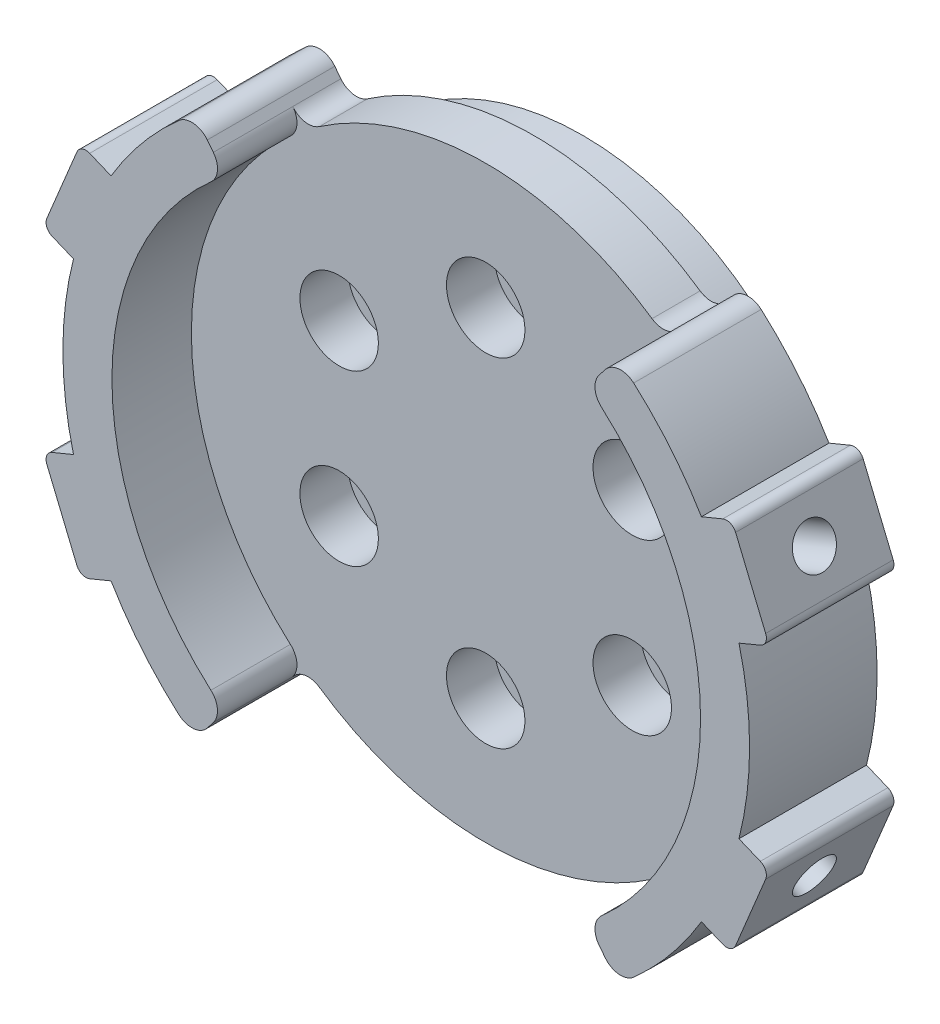
SolidWorks part; units mm, degrees
ref_plane "前视基准面" through (0, 0, 0) normal (0, 0, 1) x (1, 0, 0)
ref_plane "上视基准面" through (0, 0, 0) normal (0, 1, 0) x (1, 0, 0)
ref_plane "右视基准面" through (0, 0, 0) normal (1, 0, 0) x (0, 0, -1)
other "Configuration Table"
sketch "草图1" plane through (0, 0, 0) normal (0, 0, 1) x (1, 0, 0)
  circle A1 centre (0, 0) radius 17.25 construction
  circle A2 centre (0, 17.25) radius 2.1
  circle A8 centre (0, 0) radius 30
  circle A9 centre (14.9389, 8.625) radius 2.1
  circle A10 centre (14.9389, -8.625) radius 2.1
  circle A11 centre (0, -17.25) radius 2.1
  circle A12 centre (-14.9389, -8.625) radius 2.1
  circle A13 centre (-14.9389, 8.625) radius 2.1
  point P16 (0, 0)
  point P21 (0, 0)
  dimension "D1" = 60
  dimension "D2" = 34.5
  dimension "D3" = 4.2
  dimension "D4" = 6
extrude "凸台-拉伸1" add sketch "草图1" along normal blind 5
sketch "草图2" plane through (0, 0, 5) normal (0, 0, 1) x (1, 0, 0)
  line L0 (0, 0) -> (0, 35)
  line L1 (0, 0) -> (-35, 0)
  line L2 (0, 0) -> (-21.5482, 27.5804)
  line L3 (0, 0) -> (-21.5482, -27.5804)
  line L4 (0, 0) -> (21.5482, -27.5804)
  line L5 (0, 0) -> (21.5482, 27.5804)
  circle A0 centre (0, 0) radius 35
  circle M8 centre (0, 0) radius 30
  dimension "D2" = 70
  dimension "D1" = 52
  dimension "D3" = 52
extrude "凸台-拉伸2" add sketch "草图2" along normal blind 8 and the other way blind 5 contours L1 A0 L3 M8 | L2 A0 L1 M8 | L4 A0 L5 M8
sketch "草图3" plane through (0, 0, 13) normal (0, 0, 1) x (1, 0, 0)
  line L0 (0, 0) -> (0, 30)
  line L1 (0, 0) -> (-35, 0)
  line L2 (0, 0) -> (-32.3358, 13.3939)
  line L3 (-33.194, 19.1614) -> (-37.0208, 9.9226)
  line L4 (-33.194, 19.1614) -> (-30.0907, 17.8759)
  line L5 (-37.0208, 9.9226) -> (-33.9175, 8.6371)
  line L6 (0, 0) -> (-35.1074, 14.542)
  line L7 (-33.194, -19.1614) -> (-30.0907, -17.8759)
  line L8 (-37.0208, -9.9226) -> (-33.9175, -8.6371)
  line L9 (-33.194, -19.1614) -> (-37.0208, -9.9226)
  line L10 (33.194, -19.1614) -> (30.0907, -17.8759)
  line L11 (33.194, -19.1614) -> (37.0208, -9.9226)
  line L12 (-18.4698, 23.6403) -> (-21.5482, 27.5804)
  line L13 (-21.5482, -27.5804) -> (-18.4698, -23.6403)
  line L14 (-18.4698, 23.6403) -> (-21.5482, 27.5804)
  line L15 (-21.5482, -27.5804) -> (-18.4698, -23.6403)
  line L16 (37.0208, -9.9226) -> (33.9175, -8.6371)
  line L17 (37.0208, 9.9226) -> (33.9175, 8.6371)
  line L18 (33.194, 19.1614) -> (37.0208, 9.9226)
  line L19 (33.194, 19.1614) -> (30.0907, 17.8759)
  line L22 (18.4698, -23.6403) -> (21.5482, -27.5804)
  line L23 (21.5482, 27.5804) -> (18.4698, 23.6403)
  line L24 (18.4698, -23.6403) -> (21.5482, -27.5804)
  line L25 (21.5482, 27.5804) -> (18.4698, 23.6403)
  arc A0 (-21.5482, 27.5804) -> (-21.5482, -27.5804) centre (0, 0) ccw construction
  arc A3 (-18.4698, 23.6403) -> (-18.4698, -23.6403) centre (0, 0) ccw
  arc A4 (-18.4698, 23.6403) -> (-18.4698, -23.6403) centre (0, 0) ccw
  arc A5 (-18.4698, -23.6403) -> (18.4698, -23.6403) centre (0, 0) ccw
  arc A6 (18.4698, -23.6403) -> (18.4698, 23.6403) centre (0, 0) ccw
  arc A7 (18.4698, 23.6403) -> (-18.4698, 23.6403) centre (0, 0) ccw
  arc A8 (-18.4698, 23.6403) -> (-18.4698, -23.6403) centre (0, 0) ccw
  arc A9 (-18.4698, -23.6403) -> (18.4698, -23.6403) centre (0, 0) ccw
  arc A10 (18.4698, -23.6403) -> (18.4698, 23.6403) centre (0, 0) ccw
  arc A11 (18.4698, 23.6403) -> (-18.4698, 23.6403) centre (0, 0) ccw
  arc A12 (-21.5482, 27.5804) -> (-21.5482, -27.5804) centre (0, 0) ccw
  arc A13 (-18.4698, 23.6403) -> (-18.4698, -23.6403) centre (0, 0) ccw
  arc A14 (-21.5482, 27.5804) -> (-21.5482, -27.5804) centre (0, 0) ccw
  arc A15 (21.5482, -27.5804) -> (21.5482, 27.5804) centre (0, 0) ccw
  arc A16 (18.4698, -23.6403) -> (18.4698, 23.6403) centre (0, 0) ccw
  arc A17 (21.5482, -27.5804) -> (21.5482, 27.5804) centre (0, 0) ccw
  arc A18 (18.4698, -23.6403) -> (18.4698, 23.6403) centre (0, 0) ccw
  point P17 (-35.1074, 14.542)
  arc M23 (-21.5482, 27.5804) -> (-21.5482, -27.5804) centre (0, 0) ccw
  dimension "D2" = 67.5
  dimension "D3" = 10
  dimension "D4" = 38
  dimension "D1" = 0
  dimension "D5" = 0
  dimension "D6" = 0
extrude "凸台-拉伸3" add sketch "草图3" against normal through all contours A17 L17 L18 L19 | A17 L10 L11 L16 | L9 L7 L8 M23 | L6 L4 L3 M23 | L6 L3 L5 M23
sketch "草图4" plane through (-35.1074, 14.542, 0) normal (-0.9239, 0.3827, 0) x (0, 0, 1)
  line L0 (0, 0) -> (13, 0)
  line L1 (6.5, -5) -> (6.5, 5)
  line L4 (13, -5) -> (13, 5)
  line L5 (13, 5) -> (0, 5)
  line L6 (0, 5) -> (0, -5)
  line L7 (0, -5) -> (13, -5)
  line L8 (13, -5) -> (13, 5)
  line L9 (13, 5) -> (0, 5)
  line L10 (0, 5) -> (0, -5)
  line L11 (0, -5) -> (13, -5)
  circle A0 centre (6.5, 0) radius 2.1
  dimension "D2" = 4.2
  dimension "D1" = 0
extrude "切除-拉伸2" cut sketch "草图4" against normal blind 7.5 contours L0 A0 L1 | L1 A0 L0 | L0 A0 L1 | L1 A0 L0
sketch "草图5" plane through (-35.1074, -14.542, 0) normal (-0.9239, -0.3827, 0) x (0, 0, 1)
  line L0 (0, 0) -> (13, 0)
  line L1 (13, -5) -> (13, 5) construction
  line L2 (6.5, 5) -> (6.5, -5)
  line L3 (0, 5) -> (13, 5) construction
  line L4 (0, -5) -> (13, -5) construction
  circle A0 centre (6.5, 0) radius 2.1
  dimension "D1" = 4.2
extrude "切除-拉伸3" cut sketch "草图5" against normal blind 7.5 contours L2 A0 L0 | L0 A0 L2 | L2 A0 L0 | L0 A0 L2
sketch "草图6" plane through (35.1074, 14.542, 0) normal (0.9239, 0.3827, 0) x (0, 0, -1)
  line L0 (-13, 0) -> (0, 0)
  line L4 (-13, 5) -> (-13, -5)
  line L5 (-13, -5) -> (0, -5)
  line L6 (0, -5) -> (0, 5)
  line L7 (0, 5) -> (-13, 5)
  line L8 (-13, 5) -> (-13, -5)
  line L9 (-13, -5) -> (0, -5)
  line L10 (0, -5) -> (0, 5)
  line L11 (0, 5) -> (-13, 5)
  circle A0 centre (-6.5, 0) radius 2.1
  dimension "D2" = 4.2
  dimension "D1" = 0
extrude "切除-拉伸4" cut sketch "草图6" against normal blind 7.5 contours L0 A0 | L0 A0
sketch "草图7" plane through (35.1074, -14.542, 0) normal (0.9239, -0.3827, 0) x (0, 0, -1)
  line L0 (-13, 0) -> (0, 0)
  line L4 (-13, 5) -> (-13, -5)
  line L5 (-13, -5) -> (0, -5)
  line L6 (0, -5) -> (0, 5)
  line L7 (0, 5) -> (-13, 5)
  line L8 (-13, 5) -> (-13, -5)
  line L9 (-13, -5) -> (0, -5)
  line L10 (0, -5) -> (0, 5)
  line L11 (0, 5) -> (-13, 5)
  circle A0 centre (-6.5, 0) radius 2.1
  dimension "D2" = 4.2
  dimension "D1" = 0
extrude "切除-拉伸5" cut sketch "草图7" against normal blind 7.5 contours L0 A0 | L0 A0
fillet "圆角1" radius 2 8 edges at (21.5482, -27.5804, 6.5) (18.4698, -23.6403, 9) (-21.5482, -27.5804, 6.5) (-18.4698, -23.6403, 9) (-18.4698, 23.6403, 9) (-21.5482, 27.5804, 6.5) (18.4698, 23.6403, 9) (21.5482, 27.5804, 6.5)
fillet "圆角2" radius 2 4 edges at (-18.4698, 23.6403, 2.5) (18.4698, 23.6403, 2.5) (18.4698, -23.6403, 2.5) (-18.4698, -23.6403, 2.5)
sketch "草图8" plane through (0, 0, 0) normal (0, 0, -1) x (-1, 0, 0)
  circle A0 centre (0, 0) radius 27.5
  circle A2 centre (0, 17.25) radius 2.1
  circle A3 centre (0, 17.25) radius 2.1
  circle A4 centre (-14.9389, 8.625) radius 2.1
  circle A5 centre (-14.9389, 8.625) radius 2.1
  circle A6 centre (-14.9389, -8.625) radius 2.1
  circle A7 centre (-14.9389, -8.625) radius 2.1
  circle A8 centre (0, -17.25) radius 2.1
  circle A9 centre (0, -17.25) radius 2.1
  circle A10 centre (14.9389, -8.625) radius 2.1
  circle A11 centre (14.9389, -8.625) radius 2.1
  circle A12 centre (14.9389, 8.625) radius 2.1
  circle A13 centre (14.9389, 8.625) radius 2.1
  dimension "D7" = 55
  dimension "D1" = 0
  dimension "D2" = 0
  dimension "D3" = 0
  dimension "D4" = 0
  dimension "D5" = 0
  dimension "D6" = 0
extrude "凸台-拉伸4" add sketch "草图8" along normal blind 5 contours A0 | A7 | A9 | A5 | A13 | A11 | A3
sketch "草图9" plane through (0, 0, 5) normal (0, 0, 1) x (1, 0, 0)
  circle A0 centre (-14.9389, 8.625) radius 4
  circle A1 centre (0, 17.25) radius 2.1
  circle A2 centre (0, 17.25) radius 2.1
  circle A3 centre (14.9389, 8.625) radius 2.1
  circle A4 centre (14.9389, 8.625) radius 2.1
  circle A5 centre (14.9389, -8.625) radius 2.1
  circle A6 centre (14.9389, -8.625) radius 2.1
  circle A7 centre (0, -17.25) radius 2.1
  circle A8 centre (0, -17.25) radius 2.1
  circle A9 centre (-14.9389, -8.625) radius 2.1
  circle A10 centre (-14.9389, -8.625) radius 2.1
  circle A11 centre (-14.9389, 8.625) radius 2.1
  circle A12 centre (-14.9389, 8.625) radius 2.1
  circle A13 centre (0, 17.25) radius 4
  circle A14 centre (14.9389, 8.625) radius 4
  circle A15 centre (14.9389, -8.625) radius 4
  circle A16 centre (0, -17.25) radius 4
  circle A17 centre (-14.9389, -8.625) radius 4
  arc A24 (19.6627, 25.167) -> (19.9113, 22.4397) centre (21.2387, 23.9357) ccw
  arc A25 (16.9562, 24.7485) -> (19.6627, 25.167) centre (18.0866, 26.3984) ccw
  arc A26 (16.9562, 24.7485) -> (-16.9562, 24.7485) centre (0, 0) ccw
  arc A27 (-19.6627, 25.167) -> (-16.9562, 24.7485) centre (-18.0866, 26.3984) ccw
  arc A28 (-19.9113, 22.4397) -> (-19.6627, 25.167) centre (-21.2387, 23.9357) ccw
  arc A29 (-19.9113, 22.4397) -> (-19.9113, -22.4397) centre (0, 0) ccw
  arc A30 (-19.6627, -25.167) -> (-19.9113, -22.4397) centre (-21.2387, -23.9357) ccw
  arc A31 (-16.9562, -24.7485) -> (-19.6627, -25.167) centre (-18.0866, -26.3984) ccw
  arc A32 (-16.9562, -24.7485) -> (16.9562, -24.7485) centre (0, 0) ccw
  arc A33 (19.6627, -25.167) -> (16.9562, -24.7485) centre (18.0866, -26.3984) ccw
  arc A34 (19.9113, -22.4397) -> (19.6627, -25.167) centre (21.2387, -23.9357) ccw
  arc A35 (19.9113, -22.4397) -> (19.9113, 22.4397) centre (0, 0) ccw
  arc A36 (19.6627, 25.167) -> (19.9113, 22.4397) centre (21.2387, 23.9357) ccw
  arc A37 (16.9562, 24.7485) -> (19.6627, 25.167) centre (18.0866, 26.3984) ccw
  arc A38 (16.9562, 24.7485) -> (-16.9562, 24.7485) centre (0, 0) ccw
  arc A39 (-19.6627, 25.167) -> (-16.9562, 24.7485) centre (-18.0866, 26.3984) ccw
  arc A40 (-19.9113, 22.4397) -> (-19.6627, 25.167) centre (-21.2387, 23.9357) ccw
  arc A41 (-19.9113, 22.4397) -> (-19.9113, -22.4397) centre (0, 0) ccw
  arc A42 (-19.6627, -25.167) -> (-19.9113, -22.4397) centre (-21.2387, -23.9357) ccw
  arc A43 (-16.9562, -24.7485) -> (-19.6627, -25.167) centre (-18.0866, -26.3984) ccw
  arc A44 (-16.9562, -24.7485) -> (16.9562, -24.7485) centre (0, 0) ccw
  arc A45 (19.6627, -25.167) -> (16.9562, -24.7485) centre (18.0866, -26.3984) ccw
  arc A46 (19.9113, -22.4397) -> (19.6627, -25.167) centre (21.2387, -23.9357) ccw
  arc A47 (19.9113, -22.4397) -> (19.9113, 22.4397) centre (0, 0) ccw
  circle M19 centre (-14.9389, -8.625) radius 2.1
  circle M20 centre (14.9389, -8.625) radius 2.1
  circle M21 centre (0, 17.25) radius 2.1
  circle M34 centre (14.9389, 8.625) radius 2.1
  circle M35 centre (0, -17.25) radius 2.1
  circle M36 centre (-14.9389, 8.625) radius 2.1
  dimension "D8" = 8
  dimension "D9" = 8
  dimension "D10" = 8
  dimension "D11" = 8
  dimension "D12" = 8
  dimension "D13" = 8
  dimension "D1" = 0
  dimension "D2" = 0
  dimension "D3" = 0
  dimension "D4" = 0
  dimension "D5" = 0
  dimension "D6" = 0
  dimension "D7" = 0
extrude "切除-拉伸6" cut sketch "草图9" against normal offset from surface (5 mm away) 5 contours A0 M36 | A17 M19 | A13 M21 | A16 M35 | A15 M20 | A14 M34 up to face at (-17.0389, -8.625, -5)
fillet "圆角3" radius 1 8 edges at (33.194, 19.1614, 6.5) (37.0208, 9.9226, 6.5) (37.0208, -9.9226, 6.5) (33.194, -19.1614, 6.5) (-33.194, 19.1614, 6.5) (-37.0208, 9.9226, 6.5) (-33.194, -19.1614, 6.5) (-37.0208, -9.9226, 6.5)
sketch "草图10" plane through (0, 0, 5) normal (0, 0, 1) x (1, 0, 0)
  arc A12 (19.6627, 25.167) -> (19.9113, 22.4397) centre (21.2387, 23.9357) ccw
  arc A13 (16.9562, 24.7485) -> (19.6627, 25.167) centre (18.0866, 26.3984) ccw
  arc A14 (16.9562, 24.7485) -> (-16.9562, 24.7485) centre (0, 0) ccw
  arc A15 (-19.6627, 25.167) -> (-16.9562, 24.7485) centre (-18.0866, 26.3984) ccw
  arc A16 (-19.9113, 22.4397) -> (-19.6627, 25.167) centre (-21.2387, 23.9357) ccw
  arc A17 (-19.9113, 22.4397) -> (-19.9113, -22.4397) centre (0, 0) ccw
  arc A18 (-19.6627, -25.167) -> (-19.9113, -22.4397) centre (-21.2387, -23.9357) ccw
  arc A19 (-16.9562, -24.7485) -> (-19.6627, -25.167) centre (-18.0866, -26.3984) ccw
  arc A20 (-16.9562, -24.7485) -> (16.9562, -24.7485) centre (0, 0) ccw
  arc A21 (19.6627, -25.167) -> (16.9562, -24.7485) centre (18.0866, -26.3984) ccw
  arc A22 (19.9113, -22.4397) -> (19.6627, -25.167) centre (21.2387, -23.9357) ccw
  arc A23 (19.9113, -22.4397) -> (19.9113, 22.4397) centre (0, 0) ccw
  arc A24 (19.6627, 25.167) -> (19.9113, 22.4397) centre (21.2387, 23.9357) ccw
  arc A25 (16.9562, 24.7485) -> (19.6627, 25.167) centre (18.0866, 26.3984) ccw
  arc A26 (16.9562, 24.7485) -> (-16.9562, 24.7485) centre (0, 0) ccw
  arc A27 (-19.6627, 25.167) -> (-16.9562, 24.7485) centre (-18.0866, 26.3984) ccw
  arc A28 (-19.9113, 22.4397) -> (-19.6627, 25.167) centre (-21.2387, 23.9357) ccw
  arc A29 (-19.9113, 22.4397) -> (-19.9113, -22.4397) centre (0, 0) ccw
  arc A30 (-19.6627, -25.167) -> (-19.9113, -22.4397) centre (-21.2387, -23.9357) ccw
  arc A31 (-16.9562, -24.7485) -> (-19.6627, -25.167) centre (-18.0866, -26.3984) ccw
  arc A32 (-16.9562, -24.7485) -> (16.9562, -24.7485) centre (0, 0) ccw
  arc A33 (19.6627, -25.167) -> (16.9562, -24.7485) centre (18.0866, -26.3984) ccw
  arc A34 (19.9113, -22.4397) -> (19.6627, -25.167) centre (21.2387, -23.9357) ccw
  arc A35 (19.9113, -22.4397) -> (19.9113, 22.4397) centre (0, 0) ccw
  dimension "D1" = 0
extrude "切除-拉伸7" cut sketch "草图10" against normal blind 0.1 contours A24 A35 A34 A33 A32 A31 A30 A29 A28 A27 A26 A25
